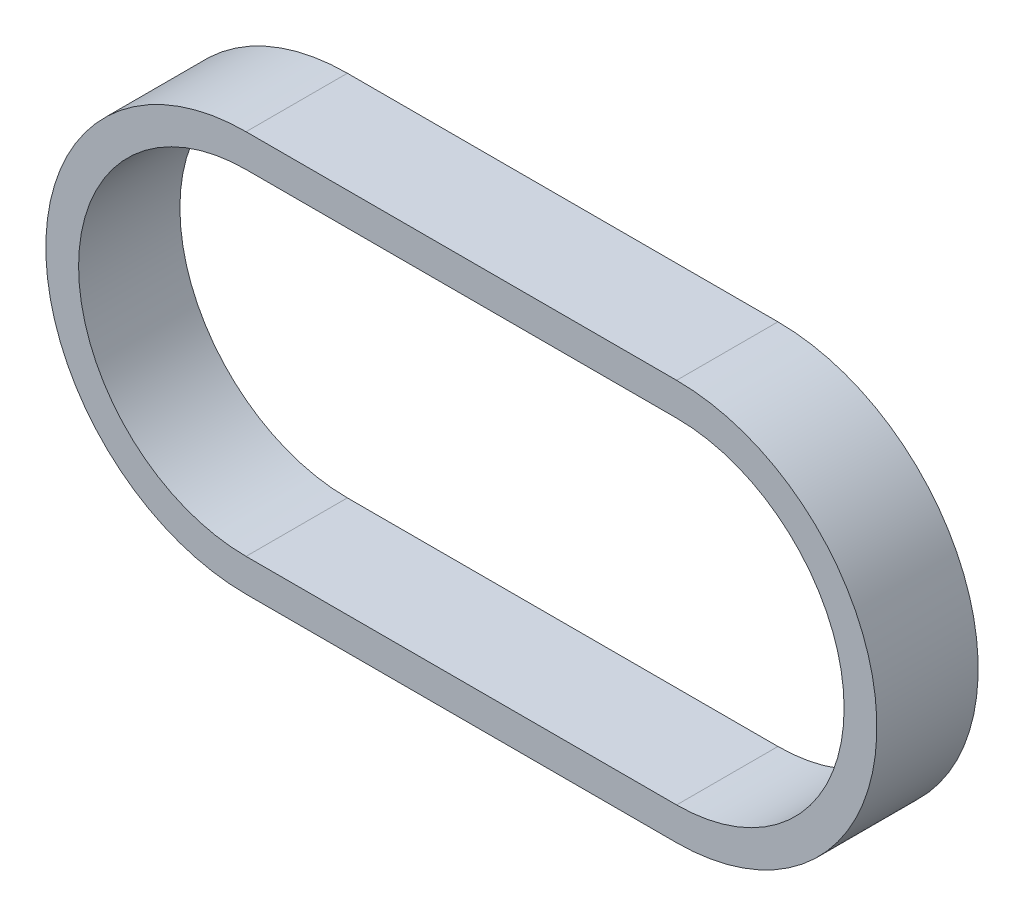
SolidWorks part; units mm, degrees
ref_plane "Plan de face" through (0, 0, 0) normal (0, 0, 1) x (1, 0, 0)
ref_plane "Plan de dessus" through (0, 0, 0) normal (0, 1, 0) x (1, 0, 0)
ref_plane "Plan de droite" through (0, 0, 0) normal (1, 0, 0) x (0, 0, -1)
sketch "Esquisse1" plane through (0, 0, 0) normal (0, 0, 1) x (1, 0, 0)
  line L0 (0, 0) -> (25.5, 0) construction
  line L1 (0, 11.46) -> (25.5, 11.46)
  line L2 (0, -11.46) -> (25.5, -11.46)
  line L3 (0, -20.2548) -> (123.0053, -20.2548) construction
  line L4 (0, 11.86) -> (25.5, 11.86)
  line L5 (0, -11.86) -> (25.5, -11.86)
  line L6 (0, 9.92) -> (25.5, 9.92)
  line L7 (0, -9.92) -> (25.5, -9.92)
  arc A0 (0, 11.46) -> (0, -11.46) centre (0, 0) ccw
  arc A1 (25.5, -11.46) -> (25.5, 11.46) centre (25.5, 0) ccw
  arc A2 (25.5, -11.86) -> (25.5, 11.86) centre (25.5, 0) ccw
  arc A3 (0, 11.86) -> (0, -11.86) centre (0, 0) ccw
  arc A4 (25.5, -9.92) -> (25.5, 9.92) centre (25.5, 0) ccw
  arc A5 (0, 9.92) -> (0, -9.92) centre (0, 0) ccw
  point P3 (12.75, 0)
  dimension "D1" = 11.46
  dimension "D3" = 36.0027
  dimension "D2" = 25.5
  dimension "D4" = 123.0053
  dimension "D5" = 0.4
  dimension "D6" = 1.54
extrude "Boss.-Extru.1" add sketch "Esquisse1" along normal mid plane 6 contours L4 A3 L5 A2 A1 L2 A0 L1 | L2 A1 L1 A0 A5 L6 A4 L7
equation "\"D4@Esquisse1\"=\"D3@Esquisse1\"+\"D3@Esquisse1\"+\"D2@Esquisse1\"+\"D2@Esquisse1\""
